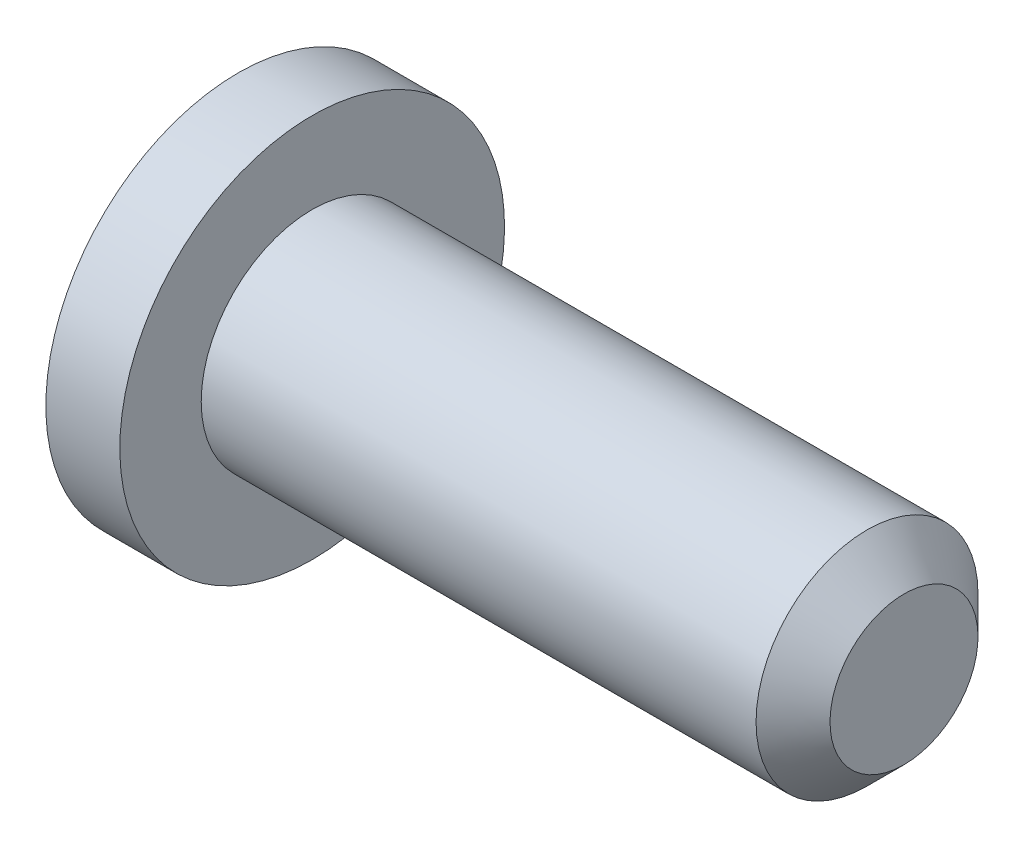
SolidWorks part; units mm, degrees
material "Легированная сталь (SS)"
ref_plane "Спереди" through (0, 0, 0) normal (0, 0, 1) x (1, 0, 0)
ref_plane "Сверху" through (0, 0, 0) normal (0, 1, 0) x (1, 0, 0)
ref_plane "Справа" through (0, 0, 0) normal (1, 0, 0) x (0, 0, -1)
sketch "Эскиз1" plane through (0, 0, 0) normal (0, 0, 1) x (1, 0, 0)
  line L0 (-8, 1.5) -> (0, 1.5)
  line L1 (-8, 1.5) -> (-8, 2.6)
  line L2 (-9, 2.6) -> (-8, 2.6)
  line L3 (0, 1.5) -> (0, 0)
  line L4 (0, 0) -> (-9.7292, 0)
  line L8 (-9.7292, 0) -> (0, 0) construction
  arc A0 (-9.7292, 0) -> (-9, 2.6) centre (-4.7292, 0) cw
  dimension "D6" = 5
  dimension "D1" = 1.5
  dimension "D2" = 8
  dimension "D3" = 0
  dimension "D4" = 2.6
  dimension "D5" = 1
revolve "Повернуть1" add sketch "Эскиз1" angle 360 about L8
ref_plane "Плоскость1" through (-13, 0, 0) normal (1, 0, 0) x (0, 0, -1)
sketch "Эскиз3" plane through (-13, 0, 0) normal (1, 0, 0) x (0, 0, -1)
  line L0 (-0.25, 0.25) -> (-0.25, 1.5)
  line L2 (0.25, 0.25) -> (0.25, 1.5)
  line L3 (-0.25, 1.5) -> (0.25, 1.5)
  line L4 (0.25, 1.5) -> (0.2316, 1.5091)
  line L5 (1.5, 0.25) -> (1.5, -0.25)
  line L6 (0.25, 0.25) -> (1.5, 0.25)
  line L7 (0.25, -0.25) -> (1.5, -0.25)
  line L8 (0.25, -1.5) -> (-0.25, -1.5)
  line L9 (0.25, -0.25) -> (0.25, -1.5)
  line L10 (-0.25, -0.25) -> (-0.25, -1.5)
  line L11 (-1.5, -0.25) -> (-1.5, 0.25)
  line L12 (-0.25, -0.25) -> (-1.5, -0.25)
  line L13 (-0.25, 0.25) -> (-1.5, 0.25)
  point P23 (0, 0)
  dimension "D1" = 0.25
  dimension "D4" = 4
extrude "Вырез-Вытянуть1" cut sketch "Эскиз3" along normal blind 4.5 contours L3 L0 L13 L11 L12 L10 L8 L9 L7 L5 L6 L2
chamfer "Фаска1" distance 0.5 angle 45 1 edges at (0, -1.5, 0)
